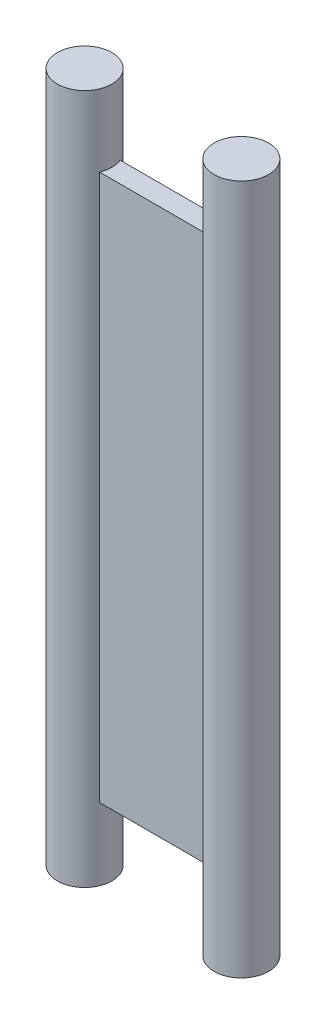
SolidWorks part; units mm, degrees
ref_plane "Front Plane" through (0, 0, 0) normal (0, 0, 1) x (1, 0, 0)
ref_plane "Top Plane" through (0, 0, 0) normal (0, 1, 0) x (1, 0, 0)
ref_plane "Right Plane" through (0, 0, 0) normal (1, 0, 0) x (0, 0, -1)
sketch "Sketch1" plane through (0, 0, 0) normal (0, 1, 0) x (1, 0, 0)
  line L1 (3.803, 0.5) -> (-3.803, 0.5)
  line L2 (3.803, 0.5) -> (3.803, -0.5)
  line L3 (3.803, -0.5) -> (-3.803, -0.5)
  line L4 (-3.803, 0.5) -> (-3.803, -0.5)
  line L5 (3.803, 0.5) -> (-3.803, -0.5) construction
  line L6 (3.803, -0.5) -> (-3.803, 0.5) construction
  point P0 (0, 0)
  dimension "D1" = 7.606
  dimension "D3" = 1
extrude "Boss-Extrude1" add sketch "Sketch1" along normal blind 26.5
ref_plane "Plane1" through (0, 13.25, 0) normal (0, 1, 0) x (1, 0, 0)
sketch "Sketch2" plane through (0, 13.25, 0) normal (0, 1, 0) x (1, 0, 0)
  line L0 (3.803, -0.5) -> (3.803, 0.5) construction
  line L1 (-3.803, 0.5) -> (-3.803, -0.5) construction
  line L2 (3.803, -0.5) -> (3.803, 0.5) construction
  line L3 (-3.803, 0.5) -> (-3.803, -0.5) construction
  circle A0 centre (-3.803, 0) radius 1.325
  circle A1 centre (3.803, 0) radius 1.325
  dimension "D1" = 2.65
extrude "Boss-Extrude2" add sketch "Sketch2" along normal mid plane 33.5
